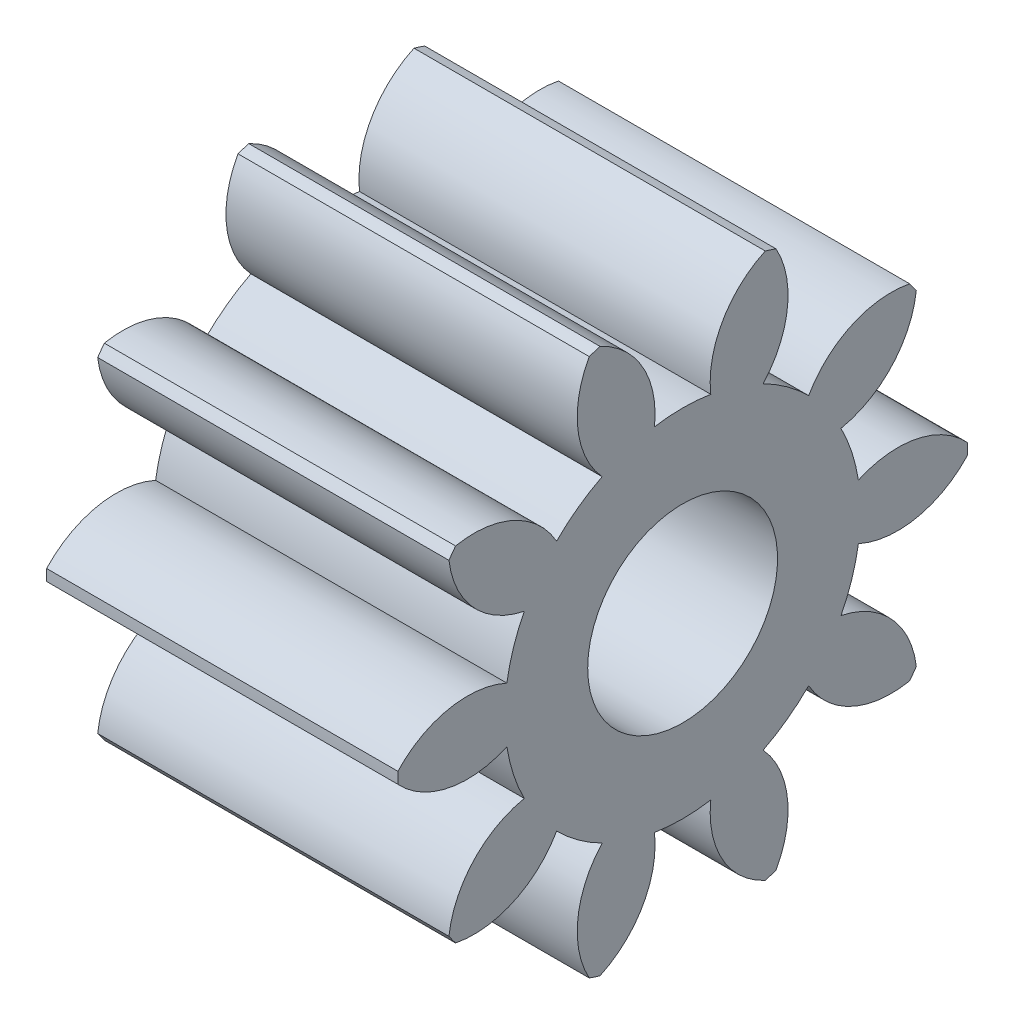
SolidWorks part; units mm, degrees
ref_plane "Plane1" through (0, 0, 0) normal (0, 0, 1) x (1, 0, 0)
ref_plane "Plane2" through (0, 0, 0) normal (0, 1, 0) x (1, 0, 0)
ref_plane "Plane3" through (0, 0, 0) normal (1, 0, 0) x (0, 0, -1)
sketch "HoldingSke" plane through (0, 0, 0) normal (0, 1, 0) x (1, 0, 0)
  line L0 (0, 0) -> (1.9696, -0.3473)
  line L1 (-15, 0) -> (100, 0) construction
  line L2 (0, 0) -> (-2.1039, 2.3779)
  line L3 (0, 0) -> (-11.863, 4.5341)
  line L4 (0, 0) -> (8.5048, 1.4996)
  line L5 (0, 0) -> (-46.8476, -17.4728)
  line L6 (0, 0) -> (-1.6579, -1.1186)
  line L7 (-2.1039, 2.3779) -> (8.6586, 51.2059)
  line L8 (-76.2, 54.61) -> (-75.9, 54.61)
  line L9 (-71.009, 38.7566) -> (-53.1078, 45.2721)
  line L10 (-76.2, 71.12) -> (104.1128, 71.12)
  line L11 (0, 0) -> (-2, 0)
  line L12 (-76.2, 101.6) -> (-76.181, 101.6)
  line L13 (24.9733, 27.94) -> (52.9518, 28.4284)
  line L14 (24.9733, 27.94) -> (24.9743, 27.94)
  line L15 (24.9733, 27.94) -> (100.4006, 29.5858)
  line L16 (-63.627, -0.5) -> (-12.827, -0.5)
  circle A0 centre (0, 0) radius 1
  circle A1 centre (0, 0) radius 1.874
  circle A2 centre (0, 0) radius 37.5
  circle A3 centre (0, 0) radius 1
  dimension "MHD" = 3.748
  dimension "Hub_dia" = 75
  dimension "Bore" = 2
  dimension "MBD" = 2
  dimension "Num_teeth" = 10
  dimension "Pitch" = 2
  dimension "Overall_len" = 50
  dimension "Show_teeth" = 10
  dimension "Thickness" = 2
  dimension "OAL" = 50.0001
  dimension "T_dim" = 0.3
  dimension "Ap" = 20
  dimension "H" = 19.05
  dimension "Pitch_radius" = 180.3128
  dimension "Width" = 2
  dimension "Backlash" = 0.019
  dimension "Addendum_fac" = 1
  dimension "Dedendum_fac" = 1.25
  dimension "Clearance_fac" = 0.25
  dimension "Dedendum_add" = 0.001
  dimension "Module" = 0.5
sketch "BasProSke" plane through (0, 0, 0) normal (0, 1, 0) x (1, 0, 0)
  line L0 (-10, 0) -> (60, 0) construction
  line L1 (0, 0) -> (0, 3)
  line L2 (0, 0) -> (3.7, 0)
  line L3 (3.7, 0) -> (3.7, 3)
  line L4 (3.7, 3) -> (0, 3)
  dimension "Thickness" = 3.7
  dimension "Diameter" = 6
revolve "Base-Revolve" add sketch "BasProSke" angle 360 about L0
sketch "TooCutSke" plane through (0, 0, 0) normal (1, 0, 0) x (0, 0, -1)
  line L1 (0, 0) -> (0, 107) construction
  line L2 (0, 0) -> (-0.4243, 2.4637) construction
  line L3 (0, 0) -> (-1.5292, 4.7063) construction
  line L4 (-0.4243, 2.4637) -> (-0.7646, 2.3532) construction
  arc A0 (0.2964, 1.8504) -> (-0.2964, 1.8504) centre (0, 0) ccw
  arc A1 (0.9059, 2.8866) -> (-0.9059, 2.8866) centre (0, 0) ccw
  circle A2 centre (0, 0) radius 2.5 construction
  circle A3 centre (0, 0) radius 2.3492 construction
  arc A4 (-0.2964, 1.8504) -> (-0.9059, 2.8866) centre (-1.2901, 1.9633) ccw
  arc A5 (0.9059, 2.8866) -> (0.2964, 1.8504) centre (1.2901, 1.9633) ccw
  dimension "Root_dia" = 3.748
  dimension "Overcut_dia" = 6.0508
  dimension "Pitch_dia" = 5
  dimension "Base_dia" = 4.6985
  dimension "Flank_rad" = 1
  dimension "Half_ang" = 18
  dimension "Half_CT" = 0.3578
extrude "ToothCut" cut sketch "TooCutSke" along normal through all
fillet "Breaks" [suppressed] radius 0.01
fillet "RootFillets" [suppressed] radius 0.126
pattern_circular "TeethCuts" count 10 every 36 about axis through (-10, 0, 0) along (1, 0, 0) of "ToothCut", "RootFillets", "Breaks"
sketch "HubNeaOneSke" plane through (0, 0, 0) normal (-1, 0, 0) x (0, 0, 1)
  circle A0 centre (0, 0) radius 1.874
  dimension "Diameter" = 3.748
extrude "HubNearOne" [suppressed] add sketch "HubNeaOneSke" along normal blind 46.3001
sketch "HubNeaBotSke" plane through (0, 0, 0) normal (-1, 0, 0) x (0, 0, 1)
  circle A0 centre (0, 0) radius 1.874
  dimension "Diameter" = 3.748
extrude "HubNearBoth" [suppressed] add sketch "HubNeaBotSke" along normal blind 23.15
ref_plane "FarPln" through (3.7, 0, 0) normal (1, 0, 0) x (0, 0, -1)
sketch "HubFarSke" plane through (3.7, 0, 0) normal (1, 0, 0) x (0, 0, -1)
  circle A0 centre (0, 0) radius 1.874
  dimension "Diameter" = 3.748
extrude "HubFar" [suppressed] add sketch "HubFarSke" along normal blind 23.15
sketch "BorSke" plane through (0, 0, 0) normal (1, 0, 0) x (0, 0, -1)
  circle A0 centre (0, 0) radius 1
  dimension "Diameter" = 2
extrude "Bore" cut sketch "BorSke" along normal mid plane 100.0001
sketch "KeySke" plane through (0, 0, 0) normal (1, 0, 0) x (0, 0, -1)
  line L0 (-0.4, 0) -> (-0.4, 1.3)
  line L1 (-0.4, 1.3) -> (0.4, 1.3)
  line L2 (0.4, 1.3) -> (0.4, 0)
  line L3 (0, 0) -> (0, 34) construction
  line L4 (-0.4, 0) -> (0.4, 0)
  dimension "Offset" = 1.3
  dimension "Width" = 0.8
extrude "Keyway" [suppressed] cut sketch "KeySke" along normal mid plane 100.0001
pattern_circular "Keyway2" [suppressed] count 2 every 90 about axis through (-10, 0, 0) along (1, 0, 0)
equation "' \"Module@HoldingSke\" = 6.35"
equation "' \"Num_teeth@HoldingSke\" = 12"
equation "' \"Ap@HoldingSke\" =  20"
equation "' \"Ap@HoldingSke\" = 20"
equation "' \"Width@HoldingSke\" = 0.5 * 25.4"
equation "' \"Hub_dia@HoldingSke\"= 1 * 25.4"
equation "' \"Hub_dia@HoldingSke\" = 1 * 25.4"
equation "' \"Overall_len@HoldingSke\" = 1.0 * 25.4"
equation "' \"Bore@HoldingSke\" = 0.75 * 25.4"
equation "' \"T_dim@HoldingSke\" = 0.1 * 25.4"
equation "' \"Width@KeySke\" = 0.25 * 25.4"
equation "' \"Show_teeth@HoldingSke\" = 13"
equation "' \"Backlash@HoldingSke\" = 0.009 * 25.4"
equation "' \"Addendum_fac@HoldingSke\" = 1.0"
equation "' \"Dedendum_fac@HoldingSke\" = 1.25"
equation "' \"Dedendum_add@HoldingSke\" = 0.00005 * 25.4"
equation "' \"Clearance_fac@HoldingSke\" = 0.25"
equation "\"Pitch@HoldingSke\" = 1 / \"Module@HoldingSke\""
equation "\"Overcut_dia@TooCutSke\" = (\"Num_teeth@HoldingSke\" + 2 * \"Addendum_fac@HoldingSke\") / \"Pitch@HoldingSke\" + 0.002 * 25.4"
equation "\"Pitch_dia@TooCutSke\" = \"Num_teeth@HoldingSke\" / \"Pitch@HoldingSke\""
equation "\"Base_dia@TooCutSke\" = \"Num_teeth@HoldingSke\" / \"Pitch@HoldingSke\" * cos((\"Ap@HoldingSke\"  * 3.14159265 / 180))"
equation "\"Root_dia@TooCutSke\" = (\"Num_teeth@HoldingSke\" + 2) / \"Pitch@HoldingSke\" - 2 * (\"Addendum_fac@HoldingSke\" + \"Dedendum_fac@HoldingSke\") / \"Pitch@HoldingSke\" - \"Dedendum_add@HoldingSke\" * 2"
equation "\"Half_ang@TooCutSke\" = 180 / \"Num_teeth@HoldingSke\""
equation "\"Half_CT@TooCutSke\" = \"Num_teeth@HoldingSke\" / \"Pitch@HoldingSke\" * sin((3.14159265 / 2 / \"Num_teeth@HoldingSke\")) / 2 - 7 * \"Backlash@HoldingSke\" / 4"
equation "\"Flank_rad@TooCutSke\" = \"Num_teeth@HoldingSke\" / \"Pitch@HoldingSke\" / 5"
equation "\"Radius@RootFillets\" = \"Clearance_fac@HoldingSke\" / \"Pitch@HoldingSke\" + \"Dedendum_add@HoldingSke\""
equation "\"Break_rad@Breaks\" = 0.02 / \"Pitch@HoldingSke\""
equation "\"Thickness@HoldingSke\" = \"Width@HoldingSke\""
equation "\"OAL@HoldingSke\" = \"Thickness@HoldingSke\""
equation "\"MHD@HoldingSke\" = (\"Num_teeth@HoldingSke\" + 2) / \"Pitch@HoldingSke\" - 2 * (\"Addendum_fac@HoldingSke\" + \"Dedendum_fac@HoldingSke\")  / \"Pitch@HoldingSke\" - \"Dedendum_add@HoldingSke\" * 2"
equation "\"MBD@HoldingSke\" = (\"Num_teeth@HoldingSke\" + 2) / \"Pitch@HoldingSke\" - 2 * (\"Addendum_fac@HoldingSke\" + \"Dedendum_fac@HoldingSke\")  / \"Pitch@HoldingSke\" - \"Dedendum_add@HoldingSke\" * 2 - 0.002 * 25.4"
equation "\"MHD@HoldingSke\" = ((sgn( \"MHD@HoldingSke\" - \"Hub_dia@HoldingSke\" )-1)*( \"MHD@HoldingSke\" - \"Hub_dia@HoldingSke\" ))/-2+ \"Hub_dia@HoldingSke\""
equation "\"MBD@HoldingSke\" = ((sgn( \"MBD@HoldingSke\" - \"Bore@HoldingSke\" )-1)*( \"MBD@HoldingSke\" - \"Bore@HoldingSke\" ))/-2+ \"Bore@HoldingSke\""
equation "\"OAL@HoldingSke\" = ((sgn( \"OAL@HoldingSke\" - \"Overall_len@HoldingSke\" )+1)*( \"OAL@HoldingSke\" - \"Overall_len@HoldingSke\" ))/2 + \"Overall_len@HoldingSke\" + 0.000002 * 25.4"
equation "\"Num_teeth@TeethCuts\" = int( \"Show_teeth@HoldingSke\" ) + 1"
equation "\"Num_teeth@TeethCuts\" = ((sgn( \"Num_teeth@TeethCuts\" - \"Num_teeth@HoldingSke\" )-1)*( \"Num_teeth@TeethCuts\" - \"Num_teeth@HoldingSke\" ))/-2+ \"Num_teeth@HoldingSke\""
equation "\"Num_teeth@TeethCuts\" = ((sgn( \"Num_teeth@TeethCuts\" - 2.0)+1)*( \"Num_teeth@TeethCuts\" - 2.0))/2 +2.0"
equation "\"Angle@TeethCuts\" = 360.0 / \"Num_teeth@HoldingSke\""
equation "\"Diameter@BasProSke\" = (\"Num_teeth@HoldingSke\" + 2 * \"Addendum_fac@HoldingSke\") / \"Pitch@HoldingSke\""
equation "\"Thickness@BasProSke\"=\"Thickness@HoldingSke\"+1.7"
equation "' \"Fillet_rad@BasProSke\" =  \"Thickness@HoldingSke\" * 0.05"
equation "' \"Fillet_rad@BasProSke\" = \"Thickness@HoldingSke\" * 0.05"
equation "\"MHD@HoldingSke\" = ((sgn( \"MHD@HoldingSke\" - \"Root_dia@TooCutSke\" )-1)*( \"MHD@HoldingSke\" - \"Root_dia@TooCutSke\" ))/-2+ \"Root_dia@TooCutSke\""
equation "\"Diameter@HubNeaOneSke\" = \"MHD@HoldingSke\""
equation "\"Length@HubNearOne\" = \"OAL@HoldingSke\" - \"Thickness@BasProSke\""
equation "\"Diameter@HubNeaBotSke\" = \"MHD@HoldingSke\""
equation "\"Length@HubNearBoth\" = ( \"OAL@HoldingSke\" - \"Thickness@BasProSke\" ) / 2.0"
equation "\"Thickness@FarPln\" = \"Thickness@BasProSke\""
equation "\"Diameter@HubFarSke\" = \"MHD@HoldingSke\""
equation "\"Length@HubFar\" = ( \"OAL@HoldingSke\" - \"Thickness@BasProSke\" ) / 2.0"
equation "\"Diameter@BorSke\" = \"MBD@HoldingSke\""
equation "\"D1@Bore\" = \"OAL@HoldingSke\" * 2.0"
equation "\"D1@Keyway\" = \"OAL@HoldingSke\" * 2.0"
equation "\"Offset@KeySke\" = \"T_dim@HoldingSke\" + \"MBD@HoldingSke\" / 2.0"
